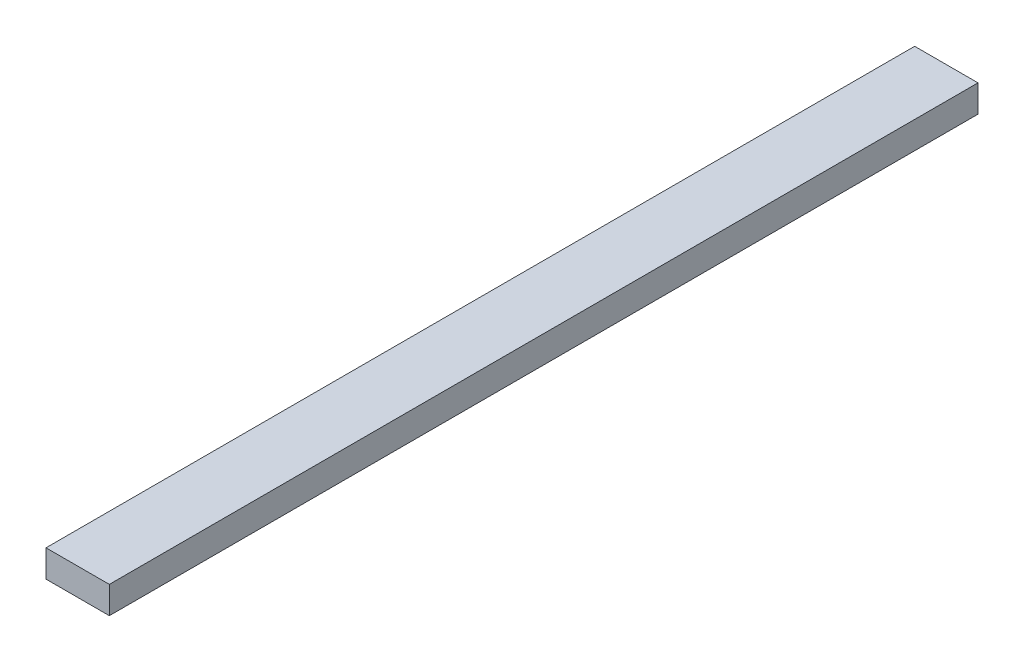
SolidWorks part; units mm, degrees
material "Pine"
ref_plane "Front Plane" through (0, 0, 0) normal (0, 0, 1) x (1, 0, 0)
ref_plane "Top Plane" through (0, 0, 0) normal (0, 1, 0) x (1, 0, 0)
ref_plane "Right Plane" through (0, 0, 0) normal (1, 0, 0) x (0, 0, -1)
sketch "Sketch1" plane through (0, 0, 0) normal (0, 0, 1) x (1, 0, 0)
  line L1 (0, 0) -> (88.9, 0)
  line L2 (0, 0) -> (0, -38.1)
  line L3 (0, -38.1) -> (88.9, -38.1)
  line L4 (88.9, 0) -> (88.9, -38.1)
  dimension "D1" = 88.9
  dimension "D2" = 38.1
extrude "Boss-Extrude1" add sketch "Sketch1" along normal blind 1219.2
equation "\"TableFrontWidth\"=48"
equation "\"TableSideWidth\"=66"
equation "\"LegWidth\"=3.5"
equation "\"LegHeight\"=30"
equation "\"LegDistToBottomStretcher\"=7"
equation "\"BottomStretcherLength\"=\"TableFrontWidth\""
equation "\"D1@Boss-Extrude1\"=\"TableFrontWidth\""
equation "\"SideStretcherLength\"=\"TableSideWidth\"-3"
equation "\"BottomSupportLength\"=\"TableSideWidth\"-3"
equation "\"BottomPlywoodFrontDim\"=\"TableFrontWidth\"-\"LegWidth\"*2-3"
equation "\"BottomPlywoodSideDim\"=\"BottomSupportLength\""
equation "\"TotalBottomSupports\"=4"
equation "\"TotalBottomSupportsLessOne\"=\"TotalBottomSupports\"-1"
equation "\"TotalTopSupports\"=5"
equation "\"TotalTopSupportsLessOne\"=\"TotalTopSupports\"-1"
equation "\"TopSupportSpread\"=\"TableFrontWidth\"-1.5"
equation "\"DistBetweenTopSupports\"=\"TopSupportSpread\"/\"TotalTopSupportsLessOne\""
equation "\"BottomSupportSpread\"= \"BottomPlywoodFrontDim\" - 1.5"
equation "\"DistBetweenBottomSupports\"=\"BottomSupportSpread\"/\"TotalBottomSupportsLessOne\""
